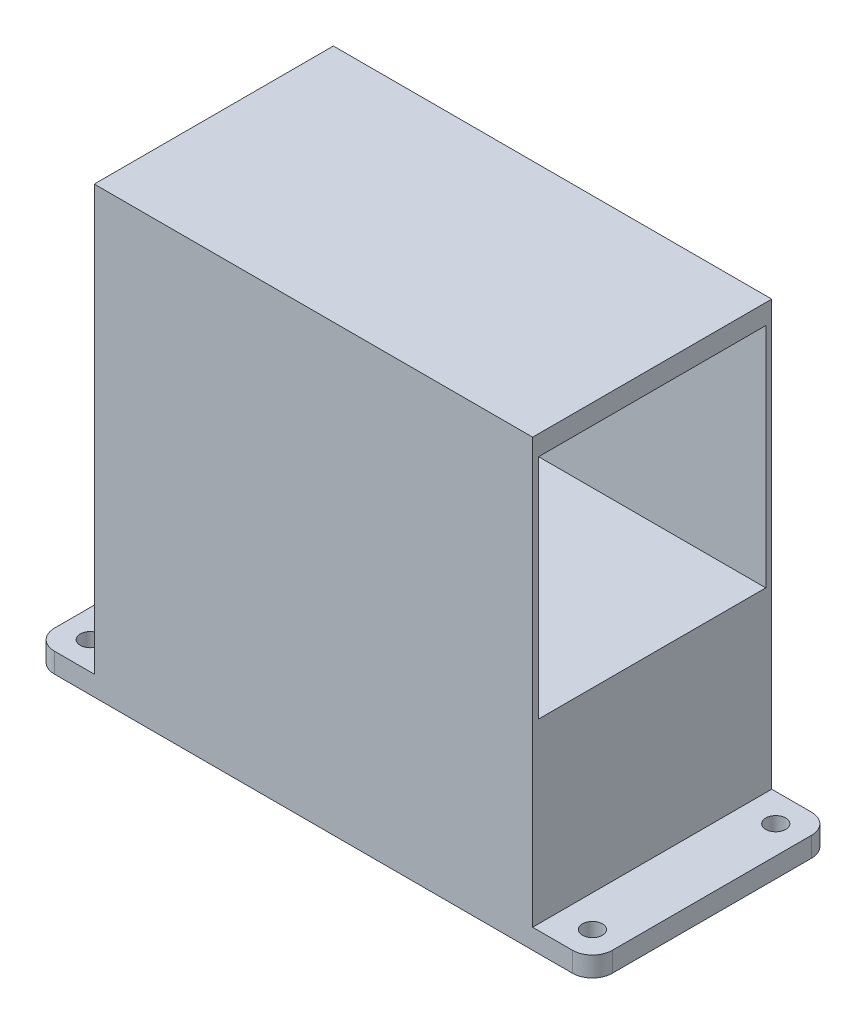
SolidWorks part; units mm, degrees
material "Q235-A"
ref_plane "前视基准面" through (0, 0, 0) normal (0, 0, 1) x (1, 0, 0)
ref_plane "上视基准面" through (0, 0, 0) normal (0, 1, 0) x (1, 0, 0)
ref_plane "右视基准面" through (0, 0, 0) normal (1, 0, 0) x (0, 0, -1)
sketch "草图1" plane through (0, 0, 0) normal (0, 1, 0) x (1, 0, 0)
  line L1 (-70, 30) -> (70, 30)
  line L2 (-70, 30) -> (-70, -30)
  line L3 (-70, -30) -> (70, -30)
  line L4 (70, 30) -> (70, -30)
  line L5 (-70, 30) -> (70, -30) construction
  line L6 (-70, -30) -> (70, 30) construction
  point P0 (0, 0)
  dimension "D1" = 140
  dimension "D2" = 60
extrude "凸台-拉伸3" add sketch "草图1" along normal blind 5
sketch "草图3" plane through (0, 5, 0) normal (0, 1, 0) x (1, 0, 0)
  line L1 (-55, -30) -> (55, -30)
  line L2 (-55, -30) -> (-55, 30)
  line L3 (-55, 30) -> (55, 30)
  line L4 (55, -30) -> (55, 30)
  line L5 (-55, -30) -> (55, 30) construction
  line L6 (-55, 30) -> (55, -30) construction
  point P0 (0, 0)
  dimension "D1" = 110
  dimension "D2" = 60
extrude "凸台-拉伸4" add sketch "草图3" along normal blind 106.5
fillet "圆角1" radius 5 4 edges at (70, 2.5, -30) (70, 2.5, 30) (-70, 2.5, 30) (-70, 2.5, -30)
sketch "草图19" plane through (-55, 0, 0) normal (-1, 0, 0) x (0, 0, 1)
  line L3 (-28.5, 49.5) -> (28.5, 49.5)
  line L4 (-28.5, 49.5) -> (-28.5, 106.5)
  line L5 (-28.5, 106.5) -> (28.5, 106.5)
  line L6 (28.5, 49.5) -> (28.5, 106.5)
  dimension "D2" = 57
  dimension "D3" = 57
extrude "切除-拉伸1" cut sketch "草图19" against normal blind 160
sketch "草图20" plane through (0, 5, 0) normal (0, 1, 0) x (1, 0, 0)
  line L1 (65, 30) -> (55, 30) construction
  line L2 (63, 30) -> (63, 23) construction
  line L3 (63, -30) -> (63, -23) construction
  line L4 (55, -30) -> (65, -30) construction
  line L5 (0, 30) -> (0, 20.5405) construction
  line L6 (55, 30) -> (-55, 30) construction
  line L7 (-63, -30) -> (-63, -23) construction
  line L8 (-63, 30) -> (-63, 23) construction
  point P6 (63, 23)
  point P7 (63, -23)
  point P15 (-63, -23)
  point P17 (-63, 23)
  dimension "D2" = 7
  dimension "D3" = 7
hole_wizard "M6 螺纹孔2" positions "草图20" profile "草图21" tap size "M6" standard "GB" end condition through all
sketch "草图21" plane through (-63, 5, -23) normal (1, 0, 0) x (0, 0, 1)
  line L0 (0, 0) -> (0, 5)
  line L1 (0, 5) -> (2.5, 5)
  line L2 (2.5, 5) -> (2.5, 0)
  line L5 (2.5, 0) -> (0, 0)
  line L11 (0, -6.35) -> (0, 107.95) construction
  dimension "通孔螺纹孔钻头直径" = 5
  dimension "通孔螺纹孔钻头深度" = 5
cosmetic thread "孔螺纹线5" parameters "D2"=6
cosmetic thread "孔螺纹线6" parameters "D2"=6
cosmetic thread "孔螺纹线7" parameters "D2"=6
cosmetic thread "孔螺纹线8" parameters "D2"=6
